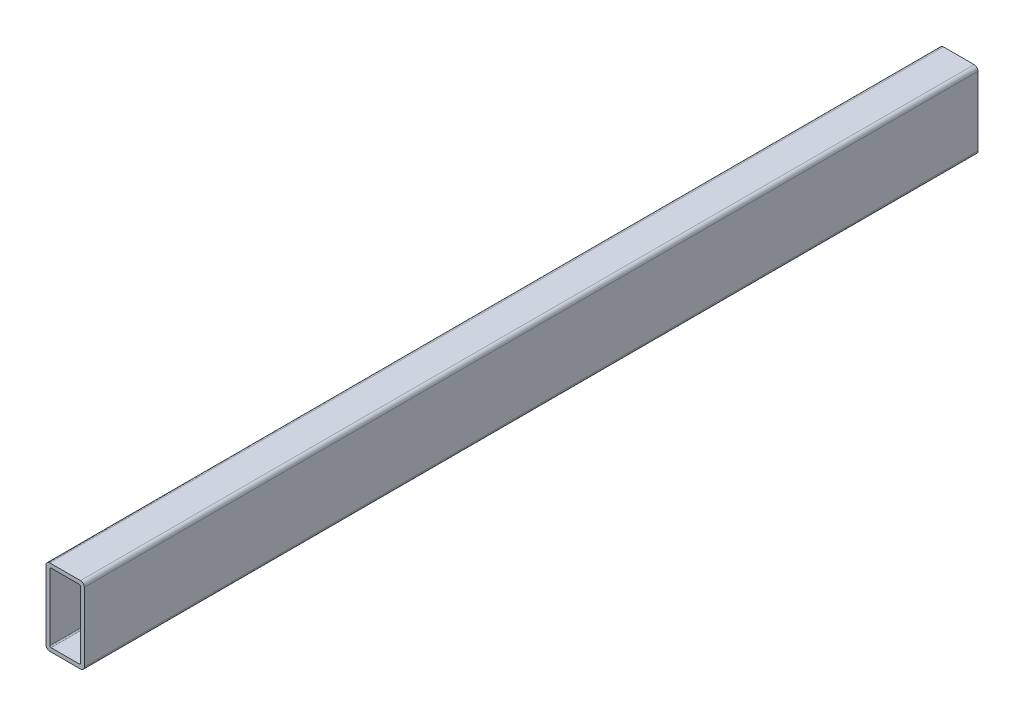
SolidWorks part; units mm, degrees
material "1.0114 (S235J0)"
ref_plane "Płaszczyzna przednia" through (0, 0, 0) normal (0, 0, 1) x (1, 0, 0)
ref_plane "Płaszczyzna górna" through (0, 0, 0) normal (0, 1, 0) x (1, 0, 0)
ref_plane "Płaszczyzna prawa" through (0, 0, 0) normal (1, 0, 0) x (0, 0, -1)
sketch "Szkic1" plane through (0, 0, 0) normal (0, 0, 1) x (1, 0, 0)
  line L0 (-11, -3) -> (11, -3)
  line L1 (-12, -60) -> (12, -60)
  line L2 (-15, -57) -> (-15, -3)
  line L3 (-12, 0) -> (12, 0)
  line L4 (15, -57) -> (15, -3)
  line L5 (12, -56) -> (12, -4)
  line L6 (-11, -57) -> (11, -57)
  line L7 (-12, -56) -> (-12, -4)
  line L8 (-15, 0) -> (15, 0) construction
  line L9 (15, -60) -> (15, 0) construction
  line L10 (-15, -60) -> (15, -60) construction
  line L11 (-15, -60) -> (-15, 0) construction
  line L12 (-12, -3) -> (12, -3) construction
  line L13 (12, -57) -> (12, -3) construction
  line L14 (-12, -57) -> (12, -57) construction
  line L15 (-12, -57) -> (-12, -3) construction
  arc A0 (12, 0) -> (15, -3) centre (12, -3) cw
  arc A1 (15, -57) -> (12, -60) centre (12, -57) cw
  arc A2 (-12, -60) -> (-15, -57) centre (-12, -57) cw
  arc A3 (-15, -3) -> (-12, 0) centre (-12, -3) cw
  arc A4 (11, -3) -> (12, -4) centre (11, -4) cw
  arc A5 (12, -56) -> (11, -57) centre (11, -56) cw
  arc A6 (-11, -57) -> (-12, -56) centre (-11, -56) cw
  arc A7 (-12, -4) -> (-11, -3) centre (-11, -4) cw
  point P12 (15, 0)
  point P34 (0, 0)
  dimension "D4" = 3
  dimension "D1" = 1
  dimension "D2" = 30
  dimension "D5" = 60
  dimension "D3" = 3
extrude "Dodanie-wyciągnięcie1" add sketch "Szkic1" against normal blind 700
sketch "Szkic2" [suppressed] plane through (15, 0, 0) normal (1, 0, 0) x (0, 0, -1)
  line L1 (0, -60) -> (34.641, -60)
  line L2 (420, -60) -> (0, -60) construction
  line L5 (420, -60) -> (420, 0)
  line L6 (420, 0) -> (385.359, -60)
  line L7 (385.359, -60) -> (420, -60)
  line L15 (34.641, -60) -> (0, 0)
  line L19 (0, -60) -> (0, 0)
  dimension "D1" = 60
  dimension "D2" = 30
extrude "Wytnij-wyciągnięcie1" [suppressed] cut sketch "Szkic2" against normal up to surface (30 mm away)
sketch "Szkic4" [suppressed] plane through (15, 0, 0) normal (1, 0, 0) x (0, 0, -1)
  line L0 (0, -60) -> (34.641, 0)
  line L1 (1700, 0) -> (0, 0) construction
  line L2 (34.641, 0) -> (0, 0)
  line L3 (0, 0) -> (0, -60)
  line L5 (1614.282, 0) -> (1614.282, -60)
  line L6 (1700, -60) -> (0, -60) construction
  line L7 (1614.282, -60) -> (1579.641, 0)
  line L8 (1579.641, 0) -> (1614.282, 0)
  line L9 (1614.282, 0) -> (1700, 0)
  line L10 (1614.282, 0) -> (1614.282, -60)
  line L11 (1614.282, -60) -> (1700, -60)
  line L12 (1700, 0) -> (1700, -60)
  dimension "D1" = 30
  dimension "D2" = 30
  dimension "D3" = 1545
extrude "Wytnij-wyciągnięcie3" [suppressed] cut sketch "Szkic4" against normal blind 373
